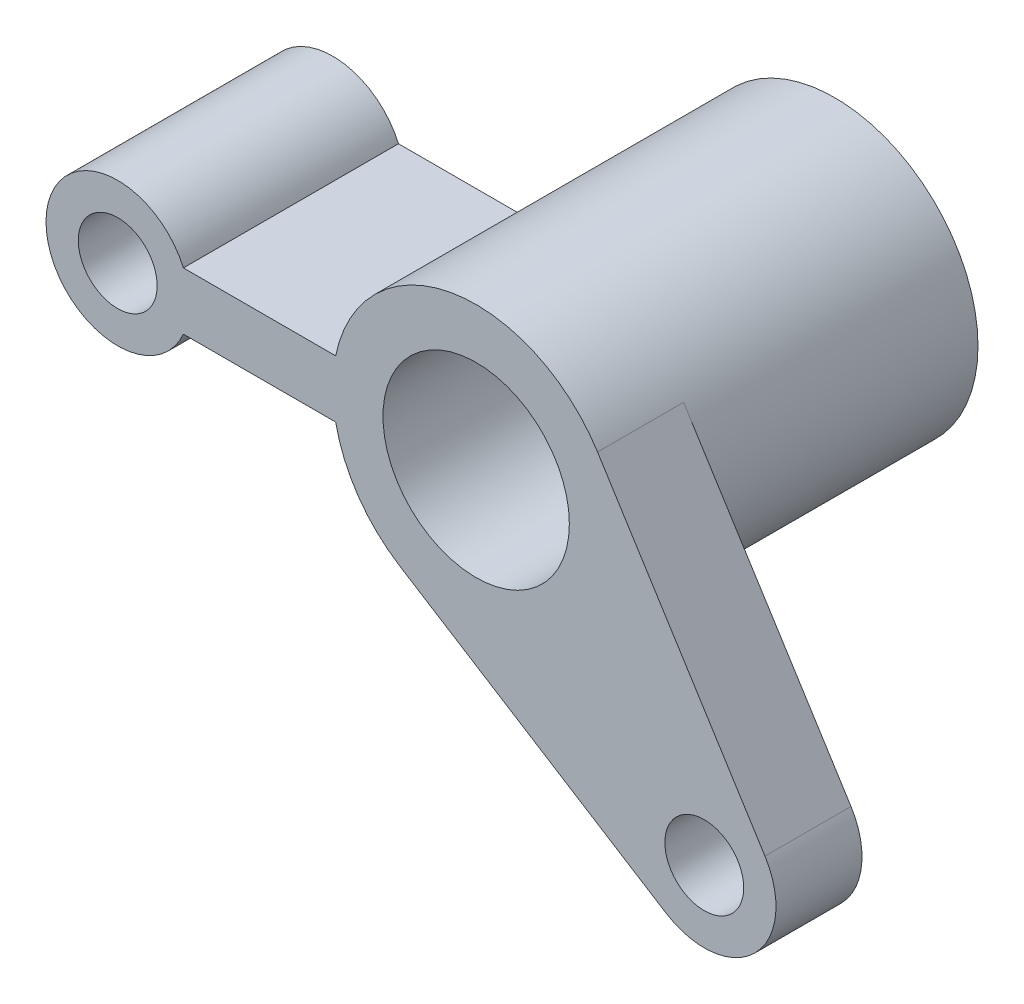
SolidWorks part; units mm, degrees
ref_plane "Спереди" through (0, 0, 0) normal (0, 0, 1) x (1, 0, 0)
ref_plane "Сверху" through (0, 0, 0) normal (0, 1, 0) x (1, 0, 0)
ref_plane "Справа" through (0, 0, 0) normal (1, 0, 0) x (0, 0, -1)
sketch "Эскиз2" plane through (0, 0, 0) normal (0, 0, 1) x (1, 0, 0)
  circle A0 centre (0, 0) radius 20
  dimension "D1" = 40
extrude "Бобышка-Вытянуть2" add sketch "Эскиз2" along normal blind 50
sketch "Эскиз3" plane through (0, 0, 50) normal (0, 0, 1) x (1, 0, 0)
  line L0 (0, 0) -> (-50, 0) construction
  line L2 (-50, -4) -> (0, -4)
  line L3 (-50, -4) -> (-50, 4)
  line L4 (-50, 4) -> (0, 4)
  line L5 (0, -4) -> (0, 4)
  line L6 (-50, -4) -> (0, 4) construction
  line L7 (-50, 4) -> (0, -4) construction
  circle A0 centre (-50, 0) radius 10
  point P3 (-25, 0)
  dimension "D2" = 20
  dimension "D1" = 50
  dimension "D3" = 8
extrude "Бобышка-Вытянуть3" add sketch "Эскиз3" against normal blind 30 contours L4 A0 L2 L3
sketch "Эскиз4" plane through (0, 0, 50) normal (0, 0, 1) x (1, 0, 0)
  line L0 (0, 0) -> (31.8198, -31.8198) construction
  line L1 (0, 0) -> (20, 0) construction
  line L2 (26.4969, -40.2854) -> (-10.6458, -16.9312)
  line L3 (40.2854, -26.4969) -> (16.9312, 10.6458)
  line L4 (-10.6458, -16.9312) -> (16.9312, 10.6458)
  circle A0 centre (31.8198, -31.8198) radius 10
  arc A1 (-19.5959, -4) -> (-19.5959, 4) centre (0, 0) ccw construction
  arc M1 (-19.5959, -4) -> (-19.5959, 4) centre (0, 0) ccw
  dimension "D3" = 20
  dimension "D1" = 45
  dimension "D2" = 45
extrude "Бобышка-Вытянуть4" add sketch "Эскиз4" against normal blind 12 contours A0 L3 L2 M1 | A0
sketch "Эскиз5" plane through (0, 0, 50) normal (0, 0, 1) x (1, 0, 0)
  circle A0 centre (0, 0) radius 13
  circle A1 centre (-50, 0) radius 5.5
  circle A2 centre (31.8198, -31.8198) radius 5.5
  dimension "D1" = 26
  dimension "D2" = 11
  dimension "D3" = 11
extrude "Вырез-Вытянуть1" cut sketch "Эскиз5" against normal through all
